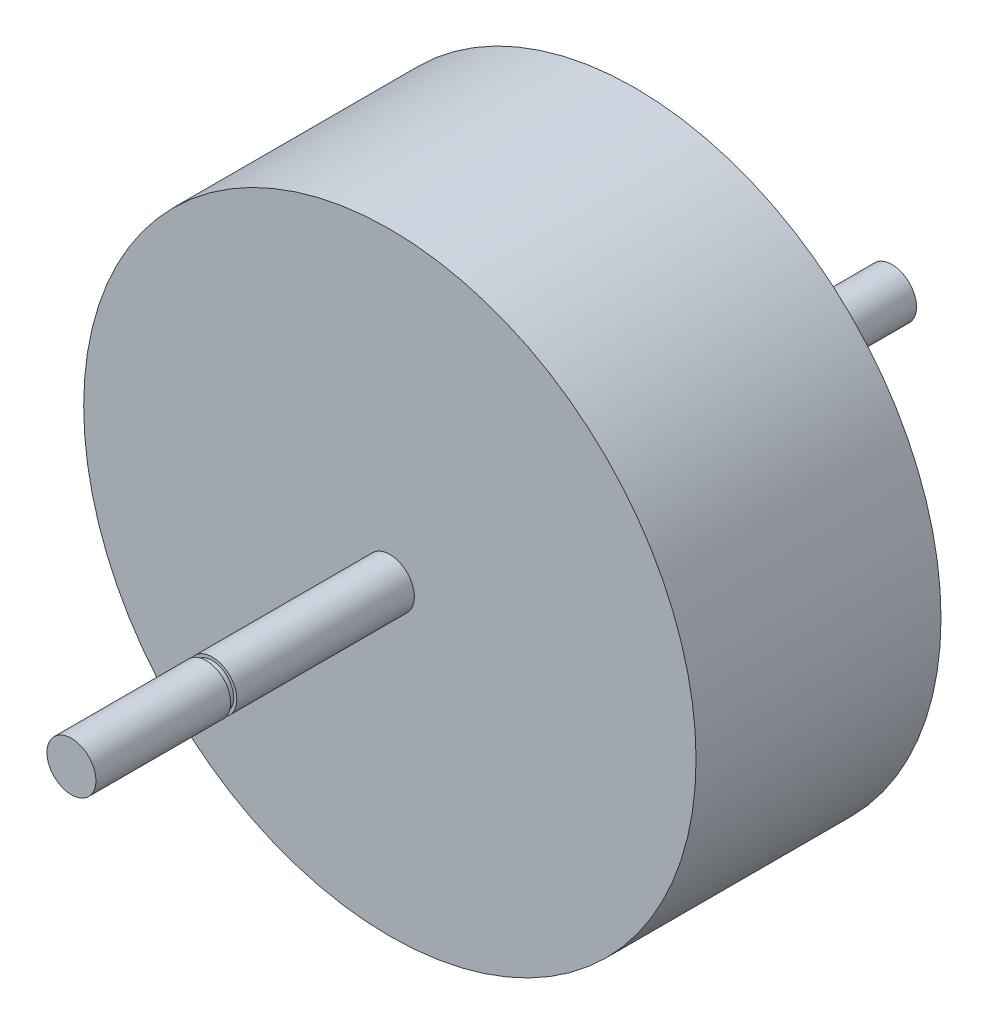
SolidWorks part; units mm, degrees
material "Rubber"
ref_plane "Front Plane" through (0, 0, 0) normal (0, 0, 1) x (1, 0, 0)
ref_plane "Top Plane" through (0, 0, 0) normal (0, 1, 0) x (1, 0, 0)
ref_plane "Right Plane" through (0, 0, 0) normal (1, 0, 0) x (0, 0, -1)
sketch "Sketch1" plane through (0, 0, 0) normal (0, 0, 1) x (1, 0, 0)
  circle A0 centre (0, 0) radius 50
  dimension "D1" = 100
  dimension "D2" = 100
extrude "Boss-Extrude1" add sketch "Sketch1" along normal mid plane 40
sketch "Sketch2" plane through (0, 0, 20) normal (0, 0, 1) x (1, 0, 0)
  circle A0 centre (0, 0) radius 4
  dimension "D1" = 8
extrude "Boss-Extrude2" add sketch "Sketch2" along normal blind 52 and the other way blind 82
ref_plane "Plane1" through (0, 0, -50) normal (0, 0, -1) x (-1, 0, 0)
sketch "Sketch3" plane through (0, 0, -50) normal (0, 0, -1) x (-1, 0, 0)
  circle A0 centre (0, 0) radius 3.5
  circle A1 centre (0, 0) radius 4
  dimension "D1" = 7
  dimension "D2" = 8
extrude "Cut-Extrude1" cut sketch "Sketch3" against normal blind 1
mirror "Mirror1" about plane through (0, 0, 0) normal (0, 0, 1) of "Cut-Extrude1"
